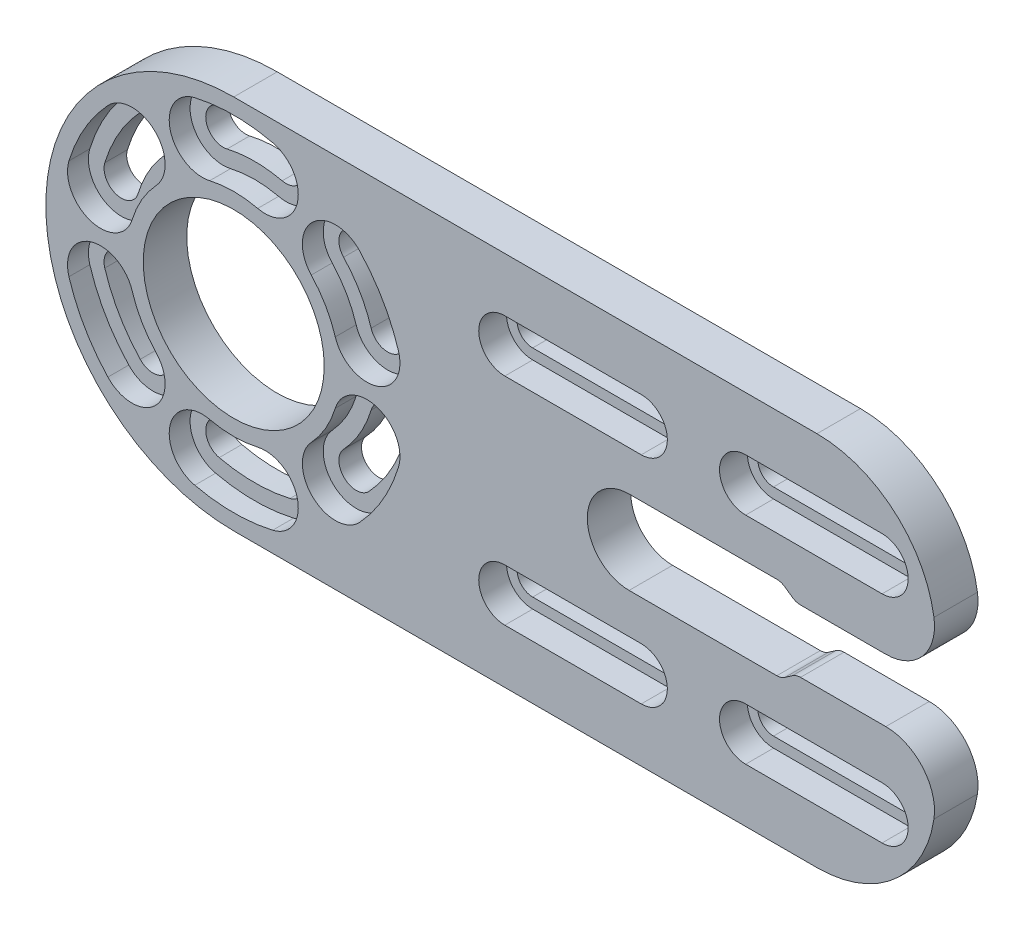
SolidWorks part; units mm, degrees
material "6061 Alloy"
ref_plane "Front Plane" through (0, 0, 0) normal (0, 0, 1) x (1, 0, 0)
ref_plane "Top Plane" through (0, 0, 0) normal (0, 1, 0) x (1, 0, 0)
ref_plane "Right Plane" through (0, 0, 0) normal (1, 0, 0) x (0, 0, -1)
sketch "Sketch1" plane through (0, 0, 0) normal (0, 0, 1) x (1, 0, 0)
  line L0 (-41.9, 0) -> (0, 0) construction
  line L1 (-41.9, 27) -> (41.9, 27)
  line L2 (-41.9, -27) -> (41.9, -27)
  line L3 (58.9, 10) -> (58.9, -10)
  line L4 (0, 0) -> (0, 27) construction
  line L5 (0, 0) -> (58.9, 0) construction
  arc A0 (-41.9, 27) -> (-41.9, -27) centre (-41.9, 0) ccw
  arc A1 (41.9, -27) -> (58.9, -10) centre (41.9, -10) ccw
  arc A2 (58.9, 10) -> (41.9, 27) centre (41.9, 10) ccw
  point P2 (0, 0)
  dimension "D1" = 27
  dimension "D2" = 127.8
  dimension "D3" = 17
extrude "Boss-Extrude1" add sketch "Sketch1" along normal blind 6.25
sketch "Sketch2" plane through (0, 0, 6.25) normal (0, 0, 1) x (1, 0, 0)
  line L0 (0, 0) -> (58.9, 0) construction
  line L1 (58.9, -10) -> (58.9, 10) construction
  line L2 (14.9, 6) -> (36.1272, 6)
  line L3 (37.2743, 5.6383) -> (38.3834, 4.8617)
  line L4 (39.5306, 4.5) -> (58.9, 4.5)
  line L5 (39.5306, -4.5) -> (58.9, -4.5)
  line L6 (37.2743, -5.6383) -> (38.3834, -4.8617)
  line L7 (14.9, -6) -> (36.1272, -6)
  line L8 (58.9, 4.5) -> (58.9, -4.5)
  circle A0 centre (-41.9, 0) radius 13
  circle A1 centre (14.9, 0) radius 6
  arc A2 (38.3834, 4.8617) -> (39.5306, 4.5) centre (39.5306, 6.5) ccw
  arc A3 (36.1272, 6) -> (37.2743, 5.6383) centre (36.1272, 4) cw
  arc A4 (36.1272, -6) -> (37.2743, -5.6383) centre (36.1272, -4) ccw
  arc A5 (38.3834, -4.8617) -> (39.5306, -4.5) centre (39.5306, -6.5) cw
  point P17 (38.9, 4.5)
  line M8 (58.9, -10) -> (58.9, 10)
  dimension "D1" = 26
  dimension "D4" = 12
  dimension "D5" = 50
  dimension "D7" = 2
  dimension "D2" = 35
  dimension "D3" = 4.5
  dimension "D6" = 30
extrude "Cut-Extrude1" cut sketch "Sketch2" against normal through all contours A1 L0 | L0 A1 | L0 A1 L7 A4 L6 A5 L5 M8 | A1 L0 L8 L4 A2 L3 A3 L2 | A0
sketch "Sketch3" plane through (0, 0, 6.25) normal (0, 0, 1) x (1, 0, 0)
  line L0 (-41.9, 20) -> (-41.9, 0) construction
  arc A0 (-46.4219, 19.4821) -> (-37.3781, 19.4821) centre (-41.9, 0) cw construction
  arc A1 (-36.3042, 24.1091) -> (-47.4958, 24.1091) centre (-41.9, 0) ccw
  arc A2 (-38.4521, 14.8551) -> (-45.3479, 14.8551) centre (-41.9, 0) ccw
  arc A3 (-38.4521, 14.8551) -> (-36.3042, 24.1091) centre (-37.3781, 19.4821) ccw
  arc A4 (-47.4958, 24.1091) -> (-45.3479, 14.8551) centre (-46.4219, 19.4821) ccw
  circle A5 centre (-41.9, 0) radius 13 construction
  arc A6 (-41.9, 27) -> (-41.9, -27) centre (-41.9, 0) ccw construction
  arc A7 (-27.2889, 13.6571) -> (-22.7671, 5.825) centre (-41.9, 0) cw construction
  arc A8 (-18.223, 7.2084) -> (-23.8188, 16.9007) centre (-41.9, 0) ccw
  arc A9 (-27.3111, 4.4416) -> (-30.7591, 10.4135) centre (-41.9, 0) ccw
  arc A10 (-27.3111, 4.4416) -> (-18.223, 7.2084) centre (-22.7671, 5.825) ccw
  arc A11 (-23.8188, 16.9007) -> (-30.7591, 10.4135) centre (-27.2889, 13.6571) ccw
  arc A12 (-22.7671, -5.825) -> (-27.2889, -13.6571) centre (-41.9, 0) cw construction
  arc A13 (-23.8188, -16.9007) -> (-18.223, -7.2084) centre (-41.9, 0) ccw
  arc A14 (-30.7591, -10.4135) -> (-27.3111, -4.4416) centre (-41.9, 0) ccw
  arc A15 (-30.7591, -10.4135) -> (-23.8188, -16.9007) centre (-27.2889, -13.6571) ccw
  arc A16 (-18.223, -7.2084) -> (-27.3111, -4.4416) centre (-22.7671, -5.825) ccw
  arc A17 (-37.3781, -19.4821) -> (-46.4219, -19.4821) centre (-41.9, 0) cw construction
  arc A18 (-47.4958, -24.1091) -> (-36.3042, -24.1091) centre (-41.9, 0) ccw
  arc A19 (-45.3479, -14.8551) -> (-38.4521, -14.8551) centre (-41.9, 0) ccw
  arc A20 (-45.3479, -14.8551) -> (-47.4958, -24.1091) centre (-46.4219, -19.4821) ccw
  arc A21 (-36.3042, -24.1091) -> (-38.4521, -14.8551) centre (-37.3781, -19.4821) ccw
  arc A22 (-56.5111, -13.6571) -> (-61.0329, -5.825) centre (-41.9, 0) cw construction
  arc A23 (-65.577, -7.2084) -> (-59.9812, -16.9007) centre (-41.9, 0) ccw
  arc A24 (-56.4889, -4.4416) -> (-53.0409, -10.4135) centre (-41.9, 0) ccw
  arc A25 (-56.4889, -4.4416) -> (-65.577, -7.2084) centre (-61.0329, -5.825) ccw
  arc A26 (-59.9812, -16.9007) -> (-53.0409, -10.4135) centre (-56.5111, -13.6571) ccw
  arc A27 (-61.0329, 5.825) -> (-56.5111, 13.6571) centre (-41.9, 0) cw construction
  arc A28 (-59.9812, 16.9007) -> (-65.577, 7.2084) centre (-41.9, 0) ccw
  arc A29 (-53.0409, 10.4135) -> (-56.4889, 4.4416) centre (-41.9, 0) ccw
  arc A30 (-53.0409, 10.4135) -> (-59.9812, 16.9007) centre (-56.5111, 13.6571) ccw
  arc A31 (-65.577, 7.2084) -> (-56.4889, 4.4416) centre (-61.0329, 5.825) ccw
  point P3 (-41.9, 20)
  point P19 (-24.5795, 10)
  point P26 (-24.5795, -10)
  point P33 (-41.9, -20)
  point P40 (-59.2205, -10)
  point P47 (-59.2205, 10)
  point P52 (-41.9, 0)
  dimension "D1" = 2.25
  dimension "D2" = 2.25
  dimension "D4" = 11.65
  dimension "D3" = 6
extrude "Cut-Extrude2" cut sketch "Sketch3" against normal blind 3
sketch "Sketch4" plane through (0, 0, 3.25) normal (0, 0, 1) x (1, 0, 0)
  arc A8 (-25.4625, 15.3643) -> (-29.1153, 11.95) centre (-27.2889, 13.6571) ccw
  arc A9 (-20.3754, 6.5531) -> (-25.4625, 15.3643) centre (-41.9, 0) ccw
  arc A10 (-25.1587, 5.0969) -> (-20.3754, 6.5531) centre (-22.7671, 5.825) ccw
  arc A11 (-25.1587, 5.0969) -> (-29.1153, 11.95) centre (-41.9, 0) ccw
  arc A12 (-37.9434, 17.0468) -> (-36.8129, 21.9174) centre (-37.3781, 19.4821) ccw
  arc A13 (-36.8129, 21.9174) -> (-46.9871, 21.9174) centre (-41.9, 0) ccw
  arc A14 (-46.9871, 21.9174) -> (-45.8566, 17.0468) centre (-46.4219, 19.4821) ccw
  arc A15 (-37.9434, 17.0468) -> (-45.8566, 17.0468) centre (-41.9, 0) ccw
  arc A16 (-37.9434, 17.0468) -> (-36.8129, 21.9174) centre (-37.3781, 19.4821) ccw
  arc A17 (-36.8129, 21.9174) -> (-46.9871, 21.9174) centre (-41.9, 0) ccw
  arc A18 (-46.9871, 21.9174) -> (-45.8566, 17.0468) centre (-46.4219, 19.4821) ccw
  arc A19 (-37.9434, 17.0468) -> (-45.8566, 17.0468) centre (-41.9, 0) ccw
  arc A20 (-20.3754, -6.5531) -> (-25.1587, -5.0969) centre (-22.7671, -5.825) ccw
  arc A21 (-25.4625, -15.3643) -> (-20.3754, -6.5531) centre (-41.9, 0) ccw
  arc A22 (-29.1153, -11.95) -> (-25.4625, -15.3643) centre (-27.2889, -13.6571) ccw
  arc A23 (-29.1153, -11.95) -> (-25.1587, -5.0969) centre (-41.9, 0) ccw
  arc A24 (-36.8129, -21.9174) -> (-37.9434, -17.0468) centre (-37.3781, -19.4821) ccw
  arc A25 (-46.9871, -21.9174) -> (-36.8129, -21.9174) centre (-41.9, 0) ccw
  arc A26 (-45.8566, -17.0468) -> (-46.9871, -21.9174) centre (-46.4219, -19.4821) ccw
  arc A27 (-45.8566, -17.0468) -> (-37.9434, -17.0468) centre (-41.9, 0) ccw
  arc A28 (-58.3375, -15.3643) -> (-54.6847, -11.95) centre (-56.5111, -13.6571) ccw
  arc A29 (-63.4246, -6.5531) -> (-58.3375, -15.3643) centre (-41.9, 0) ccw
  arc A30 (-58.6413, -5.0969) -> (-63.4246, -6.5531) centre (-61.0329, -5.825) ccw
  arc A31 (-58.6413, -5.0969) -> (-54.6847, -11.95) centre (-41.9, 0) ccw
  arc A32 (-63.4246, 6.5531) -> (-58.6413, 5.0969) centre (-61.0329, 5.825) ccw
  arc A33 (-58.3375, 15.3643) -> (-63.4246, 6.5531) centre (-41.9, 0) ccw
  arc A34 (-54.6847, 11.95) -> (-58.3375, 15.3643) centre (-56.5111, 13.6571) ccw
  arc A35 (-54.6847, 11.95) -> (-58.6413, 5.0969) centre (-41.9, 0) ccw
  point P40 (-41.9, 0)
  dimension "D1" = 2.25
  dimension "D2" = 6
extrude "Cut-Extrude3" cut sketch "Sketch4" against normal through all
fillet "Fillet1" radius 7 2 edges at (58.9, -4.5, 3.125) (58.9, 4.5, 3.125)
sketch "Sketch5" plane through (0, 0, 6.25) normal (0, 0, 1) x (1, 0, 0)
  line L0 (-2.95, 15.5) -> (16.65, 15.5) construction
  line L1 (-2.95, 19.25) -> (16.65, 19.25)
  line L2 (-2.95, 11.75) -> (16.65, 11.75)
  line L3 (41.9, 27) -> (-41.9, 27) construction
  line L4 (24.15, 27) -> (24.15, -27) construction
  line L5 (51.25, 15.5) -> (31.65, 15.5) construction
  line L6 (51.25, 19.25) -> (31.65, 19.25)
  line L7 (51.25, 11.75) -> (31.65, 11.75)
  line L9 (0, 0) -> (24.15, 0) construction
  line L10 (-41.9, -27) -> (41.9, -27) construction
  line L11 (51.25, -15.5) -> (31.65, -15.5) construction
  line L12 (51.25, -19.25) -> (31.65, -19.25)
  line L13 (51.25, -11.75) -> (31.65, -11.75)
  line L14 (-2.95, -15.5) -> (16.65, -15.5) construction
  line L15 (-2.95, -19.25) -> (16.65, -19.25)
  line L16 (-2.95, -11.75) -> (16.65, -11.75)
  arc A0 (-2.95, 19.25) -> (-2.95, 11.75) centre (-2.95, 15.5) ccw
  arc A1 (16.65, 11.75) -> (16.65, 19.25) centre (16.65, 15.5) ccw
  arc A2 (51.25, 19.25) -> (51.25, 11.75) centre (51.25, 15.5) cw
  arc A3 (31.65, 11.75) -> (31.65, 19.25) centre (31.65, 15.5) cw
  arc A4 (14.9, 6) -> (14.9, -6) centre (14.9, 0) ccw construction
  arc A5 (51.25, -19.25) -> (51.25, -11.75) centre (51.25, -15.5) ccw
  arc A6 (31.65, -11.75) -> (31.65, -19.25) centre (31.65, -15.5) ccw
  arc A7 (-2.95, -19.25) -> (-2.95, -11.75) centre (-2.95, -15.5) cw
  arc A8 (16.65, -11.75) -> (16.65, -19.25) centre (16.65, -15.5) cw
  point P2 (6.85, 15.5)
  point P13 (41.45, 15.5)
  point P30 (41.45, -15.5)
  point P37 (6.85, -15.5)
  dimension "D3" = 23.35
  dimension "D4" = 7.5
  dimension "D5" = 11.5
  dimension "D1" = 7.5
  dimension "D2" = 7.75
extrude "Cut-Extrude4" cut sketch "Sketch5" against normal blind 4
sketch "Sketch6" plane through (0, 0, 2.25) normal (0, 0, 1) x (1, 0, 0)
  line L0 (-2.95, 15.5) -> (16.65, 15.5) construction
  line L1 (-2.95, 17.75) -> (16.65, 17.75)
  line L2 (-2.95, 13.25) -> (16.65, 13.25)
  line L3 (31.65, 15.5) -> (51.25, 15.5) construction
  line L4 (31.65, 17.75) -> (51.25, 17.75)
  line L5 (31.65, 13.25) -> (51.25, 13.25)
  line L6 (0, 0) -> (16.65, 0) construction
  line L8 (31.65, -15.5) -> (51.25, -15.5) construction
  line L9 (31.65, -17.75) -> (51.25, -17.75)
  line L10 (31.65, -13.25) -> (51.25, -13.25)
  line L11 (-2.95, -15.5) -> (16.65, -15.5) construction
  line L12 (-2.95, -17.75) -> (16.65, -17.75)
  line L13 (-2.95, -13.25) -> (16.65, -13.25)
  arc A0 (-2.95, 17.75) -> (-2.95, 13.25) centre (-2.95, 15.5) ccw
  arc A1 (16.65, 13.25) -> (16.65, 17.75) centre (16.65, 15.5) ccw
  arc A2 (31.65, 17.75) -> (31.65, 13.25) centre (31.65, 15.5) ccw
  arc A3 (51.25, 13.25) -> (51.25, 17.75) centre (51.25, 15.5) ccw
  arc A4 (31.65, -17.75) -> (31.65, -13.25) centre (31.65, -15.5) cw
  arc A5 (51.25, -13.25) -> (51.25, -17.75) centre (51.25, -15.5) cw
  arc A6 (-2.95, -17.75) -> (-2.95, -13.25) centre (-2.95, -15.5) cw
  arc A7 (16.65, -13.25) -> (16.65, -17.75) centre (16.65, -15.5) cw
  point P2 (6.85, 15.5)
  point P10 (41.45, 15.5)
  point P23 (41.45, -15.5)
  point P30 (6.85, -15.5)
  dimension "D1" = 2.25
  dimension "D2" = 2.25
extrude "Cut-Extrude5" cut sketch "Sketch6" against normal through all
